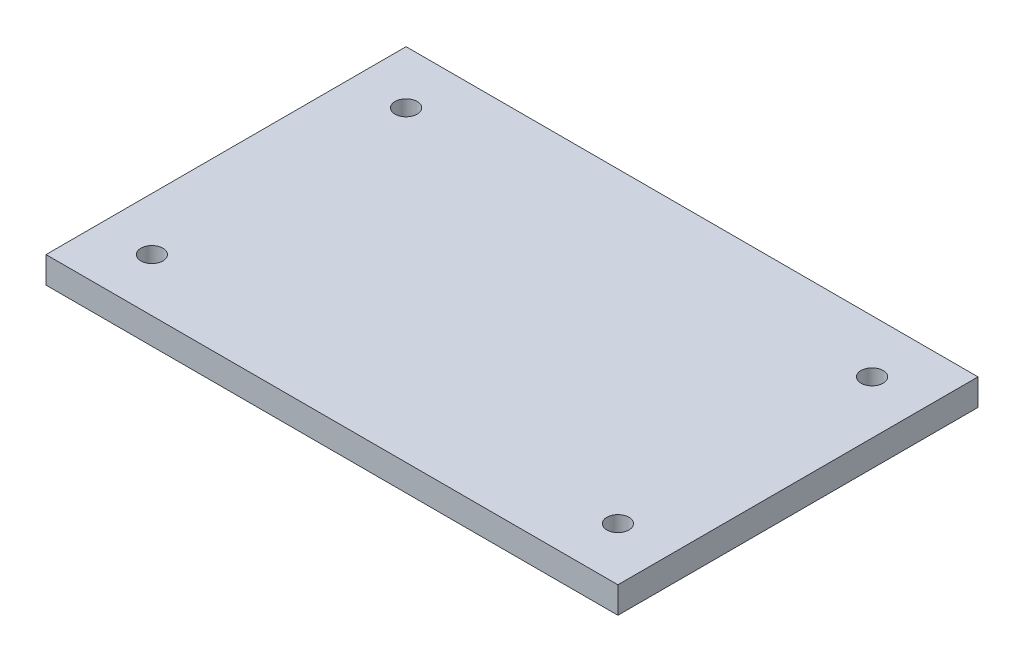
SolidWorks part; units mm, degrees
ref_plane "Front Plane" through (0, 0, 0) normal (0, 0, 1) x (1, 0, 0)
ref_plane "Top Plane" through (0, 0, 0) normal (0, 1, 0) x (1, 0, 0)
ref_plane "Right Plane" through (0, 0, 0) normal (1, 0, 0) x (0, 0, -1)
sketch "Sketch1" plane through (0, 0, 0) normal (0, 1, 0) x (1, 0, 0)
  line L0 (7.62, 7.62) -> (144.78, 7.62)
  line L1 (0, 0) -> (152.4, 0) construction
  line L2 (0, 0) -> (0, 101.6) construction
  line L3 (0, 101.6) -> (152.4, 101.6) construction
  line L4 (152.4, 0) -> (152.4, 101.6) construction
  line L5 (144.78, 7.62) -> (144.78, 93.98)
  line L6 (7.62, 93.98) -> (144.78, 93.98)
  line L7 (7.62, 7.62) -> (7.62, 93.98)
  line L8 (76.2, 93.98) -> (76.2, 7.62) construction
  line L9 (7.62, 50.8) -> (144.78, 50.8) construction
  circle A0 centre (20.32, 81.28) radius 2.5 construction
  circle A1 centre (20.32, 20.32) radius 2.5 construction
  circle A2 centre (132.08, 81.28) radius 2.5 construction
  circle A3 centre (132.08, 20.32) radius 2.5 construction
  point P15 (0, 0)
  dimension "D6" = 5
  dimension "D1" = 101.6
  dimension "D2" = 152.4
  dimension "D4" = 12.7
  dimension "D5" = 12.7
  dimension "D3" = 7.62
extrude "Boss-Extrude1" add sketch "Sketch1" along normal blind 6.35
hole_wizard "M5 Clearance Hole1" positions "Sketch2" profile "Sketch3" hole size "M5" standard "ANSI Metric" end condition through all
sketch "Sketch2" plane through (0, 6.35, 0) normal (0, 1, 0) x (1, 0, 0)
  point P0 (20.32, 81.28)
  point P3 (132.08, 81.28)
  point P6 (132.08, 20.32)
  point P9 (20.32, 20.32)
sketch "Sketch3" plane through (20.32, 6.35, -81.28) normal (1, 0, 0) x (0, 0, 1)
  line L0 (0, 0) -> (0, 6.35)
  line L1 (0, 6.35) -> (2.65, 6.35)
  line L2 (2.65, 6.35) -> (2.65, 0)
  line L5 (2.65, 0) -> (0, 0)
  line L11 (0, -6.35) -> (0, 107.95) construction
  dimension "Thru Hole Dia." = 5.3
  dimension "Thru Hole Depth" = 6.35
equation "\"L_maj\"= 6"
equation "\"L_min\"= 4"
equation "\"D1@Sketch1\"=\"L_min\""
equation "\"D2@Sketch1\"=\"L_maj\""
equation "\"Cover_scale\"= .3"
equation "\"D3@Sketch1\"=\"Cover_scale\""
equation "\"Thickness_acryllic\"= .25"
equation "\"D4@Sketch1\"=2*\"Thickness_acryllic\""
equation "\"D5@Sketch1\"=2*\"Thickness_acryllic\""
equation "\"D1@Boss-Extrude1\"=\"Thickness_acryllic\""
